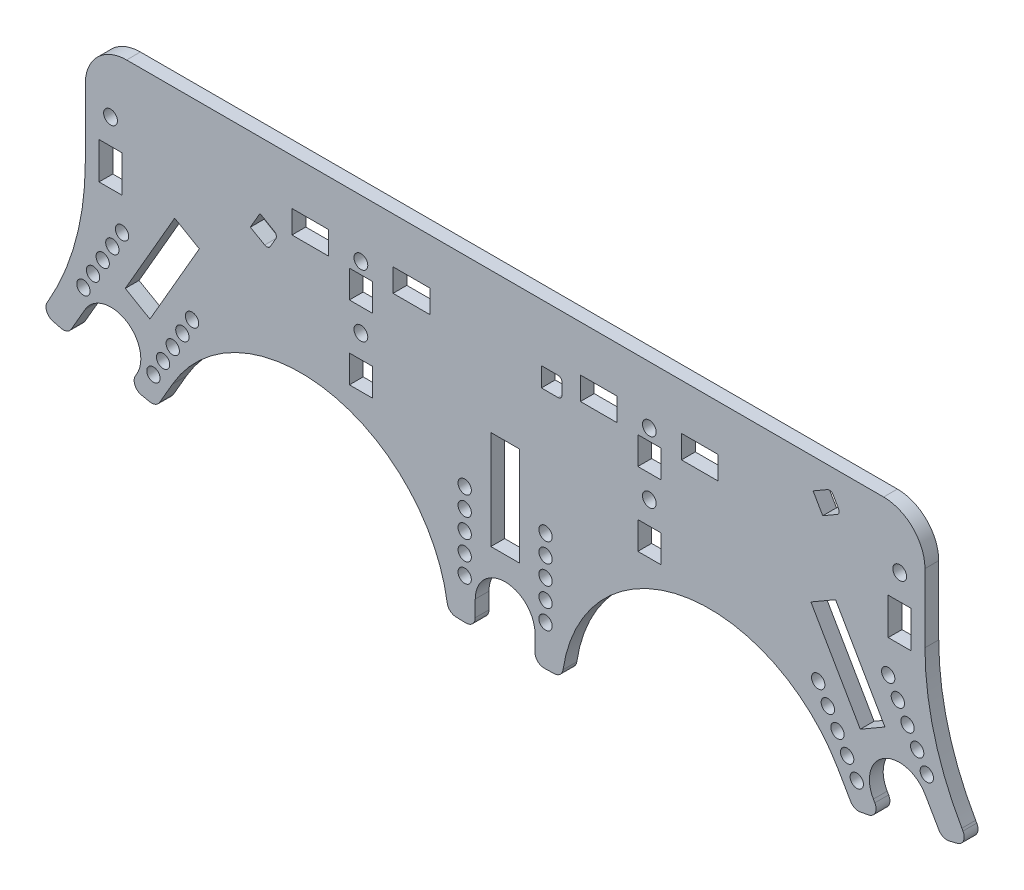
SolidWorks part; units mm, degrees
ref_plane "Front Plane" through (0, 0, 0) normal (0, 0, 1) x (1, 0, 0)
ref_plane "Top Plane" through (0, 0, 0) normal (0, 1, 0) x (1, 0, 0)
ref_plane "Right Plane" through (0, 0, 0) normal (1, 0, 0) x (0, 0, -1)
sketch "Sketch1" plane through (0, 0, 0) normal (0, 0, 1) x (1, 0, 0)
  line L0 (-12.25, 32.0854) -> (-12.25, -8)
  line L1 (-12.25, -8) -> (12.25, -8)
  line L2 (12.25, -8) -> (12.25, 32.0854)
  line L3 (12.25, 32.0854) -> (63.1039, 32.0854)
  line L4 (63.1039, 32.0854) -> (83.3912, -3.0532)
  line L5 (83.3912, -3.0532) -> (104.6088, 9.1968)
  line L6 (104.6088, 9.1968) -> (91.394, 32.0854)
  line L7 (91.394, 32.0854) -> (91.394, 72.0854)
  line L8 (91.394, 72.0854) -> (-91.394, 72.0854)
  line L9 (-91.394, 72.0854) -> (-91.394, 32.0854)
  line L10 (-91.394, 32.0854) -> (-104.6088, 9.1968)
  line L11 (-104.6088, 9.1968) -> (-83.3912, -3.0532)
  line L12 (-83.3912, -3.0532) -> (-63.1039, 32.0854)
  line L13 (-63.1039, 32.0854) -> (-12.25, 32.0854)
  line L14 (7.75, -12) -> (-7.75, -12) construction
  line L15 (102.7117, 3.4827) -> (89.2883, -4.2673) construction
  line L16 (-89.2883, -4.2673) -> (-102.7117, 3.4827) construction
  line L17 (-67.7572, 26.0256) -> (-84.5072, -2.9862) construction
  line L18 (-103.9928, 8.2638) -> (-87.2428, 37.2756) construction
  line L19 (87.2428, 37.2756) -> (103.9928, 8.2638) construction
  line L20 (84.5072, -2.9862) -> (67.7572, 26.0256) construction
  line L21 (11.25, 25) -> (11.25, -8.5) construction
  line L22 (-11.25, -8.5) -> (-11.25, 25) construction
  line L23 (-91.394, 32.0854) -> (-63.1039, 32.0854) construction
  line L24 (-12.25, 32.0854) -> (12.25, 32.0854) construction
  line L25 (63.1039, 32.0854) -> (91.394, 32.0854) construction
  line L26 (0, 72.0854) -> (0, -50.5753) construction
  circle A0 centre (0, 0) radius 33.5 construction
  circle A1 centre (-90, 10) radius 33.5 construction
  circle A2 centre (90, 10) radius 33.5 construction
  arc A3 (-72.4108, 15.9654) -> (-12.25, -0.1546) centre (-44.4901, -0.1546) cw
  arc A4 (72.4108, 15.9654) -> (12.25, -0.1546) centre (44.4901, -0.1546) ccw
  dimension "D10" = 67
  dimension "D11" = 40
  dimension "D1" = 4
  dimension "D2" = 4
  dimension "D3" = 4
  dimension "D4" = 1
  dimension "D5" = 1
  dimension "D6" = 1
  dimension "D7" = 1
  dimension "D8" = 1
  dimension "D9" = 1
extrude "Boss-Extrude1" add sketch "Sketch1" along normal blind 3 contours L12 L13 L0 L1 L2 L3 L4 L5 L6 L7 L8 L9 L10 L11 | L12 A3 L13 | L13 A3 L0 | A4 L3 L2 | A4 L4 L3
fillet "Fillet1" radius 60 2 edges at (91.394, 32.0854, 1.5) (-91.394, 32.0854, 1.5)
fillet "Fillet2" radius 8 6 edges at (-104.6088, 9.1968, 1.5) (-83.3912, -3.0532, 1.5) (-12.25, -8, 1.5) (12.25, -8, 1.5) (83.3912, -3.0532, 1.5) (104.6088, 9.1968, 1.5)
sketch "Sketch3" plane through (0, 0, 3) normal (0, 0, 1) x (1, 0, 0)
  line L8 (-53.3584, 57.6651) -> (-55.4584, 54.0278)
  line L9 (-55.4584, 54.0278) -> (-52.3407, 52.2278)
  line L10 (-51.1113, 52.5572) -> (-49.9113, 54.6357)
  line L11 (-50.2407, 55.8651) -> (-53.3584, 57.6651)
  line L12 (-53.3584, 57.6651) -> (-55.4584, 54.0278)
  line L13 (-55.4584, 54.0278) -> (-52.3407, 52.2278)
  line L14 (-51.1113, 52.5572) -> (-49.9113, 54.6357)
  line L15 (-50.2407, 55.8651) -> (-53.3584, 57.6651)
  line L16 (-68.7663, 37.5779) -> (-76.7337, 42.1779)
  line L17 (-76.7337, 42.1779) -> (-80.4837, 35.6827)
  line L18 (-80.4837, 35.6827) -> (-72.5163, 31.0827)
  line L19 (-72.5163, 31.0827) -> (-68.7663, 37.5779)
  line L20 (7.9, 59.6) -> (7.9, 55.4)
  line L21 (7.9, 55.4) -> (11.5, 55.4)
  line L22 (12.4, 56.3) -> (12.4, 58.7)
  line L23 (11.5, 59.6) -> (7.9, 59.6)
  line L24 (7.9, 59.6) -> (7.9, 55.4)
  line L25 (7.9, 55.4) -> (11.5, 55.4)
  line L26 (12.4, 56.3) -> (12.4, 58.7)
  line L27 (11.5, 59.6) -> (7.9, 59.6)
  line L32 (67.0416, 65.5651) -> (69.1416, 61.9278)
  line L33 (69.1416, 61.9278) -> (72.2593, 63.7278)
  line L34 (72.5887, 64.9572) -> (71.3887, 67.0357)
  line L35 (70.1593, 67.3651) -> (67.0416, 65.5651)
  line L36 (67.0416, 65.5651) -> (69.1416, 61.9278)
  line L37 (69.1416, 61.9278) -> (72.2593, 63.7278)
  line L38 (72.5887, 64.9572) -> (71.3887, 67.0357)
  line L39 (70.1593, 67.3651) -> (67.0416, 65.5651)
  line L40 (-68.7663, 37.5779) -> (-76.7337, 42.1779)
  line L41 (-76.7337, 42.1779) -> (-80.4837, 35.6827)
  line L42 (-80.4837, 35.6827) -> (-72.5163, 31.0827)
  line L43 (-72.5163, 31.0827) -> (-68.7663, 37.5779)
  line L48 (4.6, 34.5) -> (-4.6, 34.5)
  line L49 (-4.6, 34.5) -> (-4.6, 27)
  line L50 (-4.6, 27) -> (4.6, 27)
  line L51 (4.6, 27) -> (4.6, 34.5)
  line L52 (4.6, 34.5) -> (-4.6, 34.5)
  line L53 (-4.6, 34.5) -> (-4.6, 27)
  line L54 (-4.6, 27) -> (4.6, 27)
  line L55 (4.6, 27) -> (4.6, 34.5)
  line L60 (76.7337, 42.1779) -> (68.7663, 37.5779)
  line L61 (68.7663, 37.5779) -> (72.5163, 31.0827)
  line L62 (72.5163, 31.0827) -> (80.4837, 35.6827)
  line L63 (80.4837, 35.6827) -> (76.7337, 42.1779)
  line L64 (76.7337, 42.1779) -> (68.7663, 37.5779)
  line L65 (68.7663, 37.5779) -> (72.5163, 31.0827)
  line L66 (72.5163, 31.0827) -> (80.4837, 35.6827)
  line L67 (80.4837, 35.6827) -> (76.7337, 42.1779)
  circle A0 centre (87.596, 31.7638) radius 1.45 construction
  circle A1 centre (72.354, 22.9638) radius 1.45 construction
  circle A2 centre (8.8, 20.05) radius 1.45 construction
  circle A3 centre (-8.8, 20.05) radius 1.45 construction
  circle A4 centre (-87.596, 31.7638) radius 1.45 construction
  circle A5 centre (-72.354, 22.9638) radius 1.45 construction
  circle A6 centre (87.596, 31.7638) radius 1.45
  circle A7 centre (72.354, 22.9638) radius 1.45
  circle A8 centre (8.8, 20.05) radius 1.45
  circle A9 centre (-8.8, 20.05) radius 1.45
  circle A10 centre (-87.596, 31.7638) radius 1.45
  circle A11 centre (-72.354, 22.9638) radius 1.45
  circle A14 centre (-84.375, 19.7428) radius 3.45
  circle A15 centre (-84.375, 19.7428) radius 3.45 construction
  arc A16 (-52.3407, 52.2278) -> (-51.1113, 52.5572) centre (-51.8907, 53.0072) ccw
  arc A17 (-49.9113, 54.6357) -> (-50.2407, 55.8651) centre (-50.6907, 55.0857) ccw
  arc A18 (-52.3407, 52.2278) -> (-51.1113, 52.5572) centre (-51.8907, 53.0072) ccw
  arc A19 (-49.9113, 54.6357) -> (-50.2407, 55.8651) centre (-50.6907, 55.0857) ccw
  circle A21 centre (0, 11.25) radius 3.45
  arc A22 (11.5, 55.4) -> (12.4, 56.3) centre (11.5, 56.3) ccw
  arc A23 (12.4, 58.7) -> (11.5, 59.6) centre (11.5, 58.7) ccw
  arc A24 (11.5, 55.4) -> (12.4, 56.3) centre (11.5, 56.3) ccw
  arc A25 (12.4, 58.7) -> (11.5, 59.6) centre (11.5, 58.7) ccw
  circle A26 centre (0, 11.25) radius 3.45 construction
  arc A28 (72.2593, 63.7278) -> (72.5887, 64.9572) centre (71.8093, 64.5072) ccw
  arc A29 (71.3887, 67.0357) -> (70.1593, 67.3651) centre (70.6093, 66.5857) ccw
  arc A30 (72.2593, 63.7278) -> (72.5887, 64.9572) centre (71.8093, 64.5072) ccw
  arc A31 (71.3887, 67.0357) -> (70.1593, 67.3651) centre (70.6093, 66.5857) ccw
  circle A32 centre (84.375, 19.7428) radius 3.45
  circle A33 centre (84.375, 19.7428) radius 3.45 construction
  circle A35 centre (0, 0) radius 5.6
  circle A36 centre (0, 0) radius 5.6
  circle A38 centre (-90, 10) radius 5.6
  circle A39 centre (-90, 10) radius 5.6
  circle A41 centre (90, 10) radius 5.6
  circle A42 centre (90, 10) radius 5.6
  dimension "D1" = 0.1
  dimension "D2" = 0.1
  dimension "D3" = 0.1
  dimension "D4" = 2
  dimension "D5" = 2
  dimension "D6" = 2
  dimension "D7" = 1.5
  dimension "D8" = 1.5
  dimension "D9" = 1.5
  dimension "D10" = 2
  dimension "D11" = 2
  dimension "D12" = 2
extrude "Cut-Extrude1" cut sketch "Sketch3" against normal through all
sketch "Sketch4" plane through (0, 0, 3) normal (0, 0, 1) x (1, 0, 0)
  line L0 (84.394, 57.0854) -> (84.394, 62.0854) construction
  line L1 (29.894, 57.0854) -> (29.894, 62.0854) construction
  line L2 (32.894, 57.0854) -> (32.894, 62.0854) construction
  line L3 (87.394, 57.0854) -> (87.394, 62.0854) construction
  line L4 (-46.394, 62.0854) -> (-46.394, 57.0854)
  line L5 (-46.394, 57.0854) -> (-38.394, 57.0854)
  line L6 (-38.394, 57.0854) -> (-38.394, 62.0854)
  line L7 (-38.394, 62.0854) -> (-46.394, 62.0854)
  line L8 (-46.394, 62.0854) -> (-46.394, 57.0854)
  line L9 (-46.394, 57.0854) -> (-38.394, 57.0854)
  line L10 (-38.394, 57.0854) -> (-38.394, 62.0854)
  line L11 (-38.394, 62.0854) -> (-46.394, 62.0854)
  line L12 (-16.394, 57.0854) -> (-16.394, 62.0854)
  line L13 (-16.394, 62.0854) -> (-24.394, 62.0854)
  line L14 (-24.394, 62.0854) -> (-24.394, 57.0854)
  line L15 (-24.394, 57.0854) -> (-16.394, 57.0854)
  line L16 (-16.394, 57.0854) -> (-16.394, 62.0854)
  line L17 (-16.394, 62.0854) -> (-24.394, 62.0854)
  line L18 (-24.394, 62.0854) -> (-24.394, 57.0854)
  line L19 (-24.394, 57.0854) -> (-16.394, 57.0854)
  line L20 (16.394, 62.0854) -> (16.394, 57.0854)
  line L21 (16.394, 57.0854) -> (24.394, 57.0854)
  line L22 (24.394, 57.0854) -> (24.394, 62.0854)
  line L23 (24.394, 62.0854) -> (16.394, 62.0854)
  line L24 (16.394, 62.0854) -> (16.394, 57.0854)
  line L25 (16.394, 57.0854) -> (24.394, 57.0854)
  line L26 (24.394, 57.0854) -> (24.394, 62.0854)
  line L27 (24.394, 62.0854) -> (16.394, 62.0854)
  line L28 (46.394, 57.0854) -> (46.394, 62.0854)
  line L29 (46.394, 62.0854) -> (38.394, 62.0854)
  line L30 (38.394, 62.0854) -> (38.394, 57.0854)
  line L31 (38.394, 57.0854) -> (46.394, 57.0854)
  line L32 (46.394, 57.0854) -> (46.394, 62.0854)
  line L33 (46.394, 62.0854) -> (38.394, 62.0854)
  line L34 (38.394, 62.0854) -> (38.394, 57.0854)
  line L35 (38.394, 57.0854) -> (46.394, 57.0854)
  line L36 (-29.894, 57.0854) -> (-29.894, 62.0854) construction
  line L37 (-32.894, 57.0854) -> (-32.894, 62.0854) construction
  line L38 (-84.394, 57.0854) -> (-84.394, 62.0854) construction
  line L39 (-87.394, 57.0854) -> (-87.394, 62.0854) construction
  line L40 (-84.394, 57.0854) -> (-84.394, 62.0854) construction
  line L41 (-87.394, 57.0854) -> (-87.394, 62.0854) construction
  line L42 (84.394, 57.0854) -> (84.394, 62.0854) construction
  line L43 (-32.894, 57.0854) -> (-32.894, 62.0854) construction
  line L44 (-29.894, 57.0854) -> (-29.894, 62.0854) construction
  line L45 (87.394, 57.0854) -> (87.394, 62.0854) construction
  line L46 (32.894, 57.0854) -> (32.894, 62.0854) construction
  line L47 (29.894, 57.0854) -> (29.894, 62.0854) construction
  line L48 (-87.394, 59.5854) -> (-84.394, 59.5854) construction
  line L49 (-32.894, 59.5854) -> (-29.894, 59.5854) construction
  line L50 (29.894, 59.5854) -> (32.894, 59.5854) construction
  line L51 (84.394, 59.5854) -> (87.394, 59.5854) construction
  circle A0 centre (-31.394, 59.5854) radius 1.5
  circle A1 centre (31.394, 59.5854) radius 1.5
  circle A2 centre (-85.894, 59.5854) radius 1.5
  circle A3 centre (85.894, 59.5854) radius 1.5
  dimension "D1" = 0
  dimension "D2" = 0
  dimension "D3" = 0
  dimension "D4" = 0
extrude "Cut-Extrude2" cut sketch "Sketch4" against normal through all
sketch "Sketch5" plane through (0, 0, 3) normal (0, 0, 1) x (1, 0, 0)
  line L4 (-88.394, 54.0854) -> (-88.394, 46.0854)
  line L5 (-88.394, 46.0854) -> (-83.394, 46.0854)
  line L6 (-83.394, 46.0854) -> (-83.394, 54.0854)
  line L7 (-83.394, 54.0854) -> (-88.394, 54.0854)
  line L8 (-88.394, 54.0854) -> (-88.394, 46.0854)
  line L9 (-88.394, 46.0854) -> (-83.394, 46.0854)
  line L10 (-83.394, 46.0854) -> (-83.394, 54.0854)
  line L11 (-83.394, 54.0854) -> (-88.394, 54.0854)
  line L12 (88.394, 46.0854) -> (88.394, 54.0854)
  line L13 (88.394, 54.0854) -> (83.394, 54.0854)
  line L14 (83.394, 54.0854) -> (83.394, 46.0854)
  line L15 (83.394, 46.0854) -> (88.394, 46.0854)
  line L16 (88.394, 46.0854) -> (88.394, 54.0854)
  line L17 (88.394, 54.0854) -> (83.394, 54.0854)
  line L18 (83.394, 54.0854) -> (83.394, 46.0854)
  line L19 (83.394, 46.0854) -> (88.394, 46.0854)
  dimension "D1" = 0
  dimension "D2" = 0
extrude "Cut-Extrude3" cut sketch "Sketch5" against normal through all
fillet "Fillet3" radius 9 2 edges at (-91.394, 72.0854, 1.5) (91.394, 72.0854, 1.5)
sketch "Sketch6" plane through (0, 0, 3) normal (0, 0, 1) x (1, 0, 0)
  line L0 (-28.894, 44.5854) -> (-33.894, 44.5854) construction
  line L1 (-28.894, 47.5854) -> (-33.894, 47.5854) construction
  line L2 (28.894, 44.5854) -> (33.894, 44.5854) construction
  line L3 (28.894, 47.5854) -> (33.894, 47.5854) construction
  line L4 (33.894, 35.0854) -> (33.894, 41.0854)
  line L5 (33.894, 41.0854) -> (28.894, 41.0854)
  line L6 (28.894, 41.0854) -> (28.894, 35.0854)
  line L7 (28.894, 35.0854) -> (33.894, 35.0854)
  line L8 (33.894, 35.0854) -> (33.894, 41.0854)
  line L9 (33.894, 41.0854) -> (28.894, 41.0854)
  line L10 (28.894, 41.0854) -> (28.894, 35.0854)
  line L11 (28.894, 35.0854) -> (33.894, 35.0854)
  line L12 (33.894, 51.0854) -> (33.894, 57.0854)
  line L13 (33.894, 57.0854) -> (28.894, 57.0854)
  line L14 (28.894, 57.0854) -> (28.894, 51.0854)
  line L15 (28.894, 51.0854) -> (33.894, 51.0854)
  line L16 (33.894, 51.0854) -> (33.894, 57.0854)
  line L17 (33.894, 57.0854) -> (28.894, 57.0854)
  line L18 (28.894, 57.0854) -> (28.894, 51.0854)
  line L19 (28.894, 51.0854) -> (33.894, 51.0854)
  line L20 (-33.894, 57.0854) -> (-33.894, 51.0854)
  line L21 (-33.894, 51.0854) -> (-28.894, 51.0854)
  line L22 (-28.894, 51.0854) -> (-28.894, 57.0854)
  line L23 (-28.894, 57.0854) -> (-33.894, 57.0854)
  line L24 (-33.894, 57.0854) -> (-33.894, 51.0854)
  line L25 (-33.894, 51.0854) -> (-28.894, 51.0854)
  line L26 (-28.894, 51.0854) -> (-28.894, 57.0854)
  line L27 (-28.894, 57.0854) -> (-33.894, 57.0854)
  line L28 (-33.894, 41.0854) -> (-33.894, 35.0854)
  line L29 (-33.894, 35.0854) -> (-28.894, 35.0854)
  line L30 (-28.894, 35.0854) -> (-28.894, 41.0854)
  line L31 (-28.894, 41.0854) -> (-33.894, 41.0854)
  line L32 (-33.894, 41.0854) -> (-33.894, 35.0854)
  line L33 (-33.894, 35.0854) -> (-28.894, 35.0854)
  line L34 (-28.894, 35.0854) -> (-28.894, 41.0854)
  line L35 (-28.894, 41.0854) -> (-33.894, 41.0854)
  line L36 (-28.894, 44.5854) -> (-33.894, 44.5854) construction
  line L37 (-28.894, 47.5854) -> (-33.894, 47.5854) construction
  line L38 (28.894, 44.5854) -> (33.894, 44.5854) construction
  line L39 (28.894, 47.5854) -> (33.894, 47.5854) construction
  line L40 (-31.394, 44.5854) -> (-31.394, 47.5854) construction
  line L41 (31.394, 44.5854) -> (31.394, 47.5854) construction
  circle A0 centre (-31.394, 46.0854) radius 1.5
  circle A1 centre (31.394, 46.0854) radius 1.5
  dimension "D1" = 0
  dimension "D2" = 0
  dimension "D3" = 0
  dimension "D4" = 0
extrude "Cut-Extrude4" cut sketch "Sketch6" against normal through all
sketch "Sketch7" plane through (0, 0, 3) normal (0, 0, 1) x (1, 0, 0)
  line L3 (-75.4347, 41.4279) -> (-79.1847, 34.9327)
  line L4 (-70.0653, 38.3279) -> (-73.8153, 31.8327)
  line L5 (-72.5163, 31.0827) -> (-68.7663, 37.5779)
  line L6 (-80.4837, 35.6827) -> (-72.5163, 31.0827)
  line L7 (-76.7337, 42.1779) -> (-80.4837, 35.6827)
  line L8 (-68.7663, 37.5779) -> (-76.7337, 42.1779)
  line L9 (-72.5163, 31.0827) -> (-68.7663, 37.5779)
  line L10 (-80.4837, 35.6827) -> (-72.5163, 31.0827)
  line L11 (-76.7337, 42.1779) -> (-80.4837, 35.6827)
  line L12 (-68.7663, 37.5779) -> (-76.7337, 42.1779)
  line L13 (-3.1, 34.5) -> (-3.1, 27)
  line L14 (4.6, 27) -> (4.6, 34.5)
  line L15 (-4.6, 27) -> (4.6, 27)
  line L16 (-4.6, 34.5) -> (-4.6, 27)
  line L17 (4.6, 34.5) -> (-4.6, 34.5)
  line L18 (4.6, 27) -> (4.6, 34.5)
  line L19 (-4.6, 27) -> (4.6, 27)
  line L20 (-4.6, 34.5) -> (-4.6, 27)
  line L21 (4.6, 34.5) -> (-4.6, 34.5)
  line L22 (3.1, 34.5) -> (3.1, 27)
  line L23 (80.4837, 35.6827) -> (76.7337, 42.1779)
  line L24 (72.5163, 31.0827) -> (80.4837, 35.6827)
  line L25 (68.7663, 37.5779) -> (72.5163, 31.0827)
  line L26 (76.7337, 42.1779) -> (68.7663, 37.5779)
  line L27 (80.4837, 35.6827) -> (76.7337, 42.1779)
  line L28 (72.5163, 31.0827) -> (80.4837, 35.6827)
  line L29 (68.7663, 37.5779) -> (72.5163, 31.0827)
  line L30 (76.7337, 42.1779) -> (68.7663, 37.5779)
  line L31 (70.0653, 38.3279) -> (73.8153, 31.8327)
  line L32 (75.4347, 41.4279) -> (79.1847, 34.9327)
  dimension "D4" = 1.5
  dimension "D5" = 1.5
  dimension "D6" = 1.5
  dimension "D7" = 1.5
  dimension "D8" = 1.5
  dimension "D9" = 1.5
  dimension "D1" = 0
  dimension "D2" = 0
  dimension "D3" = 0
extrude "Boss-Extrude2" add sketch "Sketch7" against normal blind 3 contours L3 L12 L11 L10 | L9 L12 L4 L10 | L13 L21 L20 L19 | L21 L22 L19 L18 | L31 L30 L29 L28 | L30 L32 L28 L27
sketch "Sketch8" plane through (0, 0, 3) normal (0, 0, 1) x (1, 0, 0)
  line L0 (-8.8, 20.05) -> (-8.8, 2.5535) construction
  line L1 (-8.8, 2.5535) -> (-8.8, 55.0937) construction
  line L2 (8.8, 20.05) -> (8.8, 2.5535) construction
  line L3 (8.8, 2.5535) -> (8.8, 53.2094) construction
  line L4 (-94, 3.0718) -> (-76.5, 33.3827) construction
  line L5 (-97.6806, 5.1968) -> (-90.3194, 0.9468) construction
  line L6 (-79.1847, 34.9327) -> (-73.8153, 31.8327) construction
  line L7 (-72.354, 22.9638) -> (-81.927, 6.3828) construction
  line L8 (-81.927, 6.3828) -> (-61.3854, 41.9619) construction
  line L9 (-87.596, 31.7638) -> (-96.7852, 15.8477) construction
  line L10 (-96.7852, 15.8477) -> (-75.9419, 51.9493) construction
  line L11 (94, 3.0718) -> (76.5, 33.3827) construction
  line L12 (90.3194, 0.9468) -> (97.6806, 5.1968) construction
  line L13 (73.8153, 31.8327) -> (79.1847, 34.9327) construction
  line L14 (72.354, 22.9638) -> (62.3503, 40.2908) construction
  line L15 (62.3503, 40.2908) -> (89.4496, -6.6466) construction
  line L16 (87.596, 31.7638) -> (106.5379, -1.0444) construction
  line L17 (106.5379, -1.0444) -> (78.5925, 47.3584) construction
  line L18 (-8.8, 20.05) -> (-8.8, 15.85) construction
  line L19 (-72.354, 22.9638) -> (-74.454, 19.3265) construction
  line L20 (0, 34.5) -> (0, 0) construction
  line L21 (3.1, 34.5) -> (-3.1, 34.5) construction
  line L22 (0, 0) -> (21.2479, -3.7728) construction
  line L23 (72.354, 22.9638) -> (74.454, 19.3265) construction
  line L24 (8.8, 20.05) -> (8.8, 15.85) construction
  line L25 (96.7852, 15.8477) -> (75.9419, 51.9493) construction
  line L26 (87.596, 31.7638) -> (96.7852, 15.8477) construction
  line L27 (81.927, 6.3828) -> (61.3854, 41.9619) construction
  line L28 (72.354, 22.9638) -> (81.927, 6.3828) construction
  line L29 (94, 3.0718) -> (76.5, 33.3827) construction
  line L30 (8.8, 2.5535) -> (8.8, 55.0937) construction
  line L31 (8.8, 20.05) -> (8.8, 2.5535) construction
  circle A0 centre (-8.8, 20.05) radius 1.45 construction
  circle A1 centre (-8.8, 20.05) radius 1.45 construction
  circle A2 centre (-8.8, 15.85) radius 1.45
  circle A3 centre (-8.8, 11.65) radius 1.45
  circle A4 centre (-8.8, 20.05) radius 1.45
  circle A5 centre (-8.8, 15.85) radius 1.45
  circle A6 centre (-8.8, 24.25) radius 1.45
  circle A7 centre (-8.8, 20.05) radius 1.45
  circle A8 centre (-8.8, 24.25) radius 1.45
  circle A9 centre (-8.8, 28.45) radius 1.45
  circle A10 centre (-72.354, 22.9638) radius 1.45 construction
  circle A11 centre (-72.354, 22.9638) radius 1.45 construction
  circle A12 centre (-74.454, 19.3265) radius 1.45
  circle A13 centre (-76.554, 15.6892) radius 1.45
  circle A14 centre (-72.354, 22.9638) radius 1.45
  circle A15 centre (-74.454, 19.3265) radius 1.45
  circle A16 centre (-70.254, 26.6011) radius 1.45
  circle A17 centre (-72.354, 22.9638) radius 1.45
  circle A18 centre (-70.254, 26.6011) radius 1.45
  circle A19 centre (-68.154, 30.2384) radius 1.45
  circle A20 centre (-91.796, 24.4892) radius 1.45
  circle A21 centre (-89.696, 28.1265) radius 1.45
  circle A22 centre (-85.496, 35.4011) radius 1.45
  circle A23 centre (-83.396, 39.0384) radius 1.45
  circle A24 centre (83.396, 39.0384) radius 1.45
  circle A25 centre (85.496, 35.4011) radius 1.45
  circle A26 centre (89.696, 28.1265) radius 1.45
  circle A27 centre (91.796, 24.4892) radius 1.45
  circle A28 centre (68.154, 30.2384) radius 1.45
  circle A29 centre (70.254, 26.6011) radius 1.45
  circle A30 centre (72.354, 22.9638) radius 1.45 construction
  circle A31 centre (70.254, 26.6011) radius 1.45
  circle A32 centre (74.454, 19.3265) radius 1.45
  circle A33 centre (72.354, 22.9638) radius 1.45
  circle A34 centre (76.554, 15.6892) radius 1.45
  circle A35 centre (74.454, 19.3265) radius 1.45
  circle A36 centre (72.354, 22.9638) radius 1.45
  circle A37 centre (8.8, 28.45) radius 1.45
  circle A38 centre (8.8, 24.25) radius 1.45
  circle A39 centre (8.8, 20.05) radius 1.45 construction
  circle A40 centre (8.8, 24.25) radius 1.45
  circle A41 centre (8.8, 15.85) radius 1.45
  circle A42 centre (8.8, 20.05) radius 1.45
  circle A43 centre (8.8, 11.65) radius 1.45
  circle A44 centre (8.8, 15.85) radius 1.45
  circle A45 centre (8.8, 20.05) radius 1.45
  dimension "D1" = 3
  dimension "D3" = 4.2
  dimension "D6" = 4.2
  dimension "D2" = 3
  dimension "D4" = 3
  dimension "D5" = 3
extrude "Cut-Extrude5" cut sketch "Sketch8" against normal through all contours A34 | A32 | A27 | A26 | A25 | A24 | A28 | A9 | A6 | A2 | A43 | A41 | A3 | A38 | A37 | A16 | A19 | A12 | A13 | A22 | A23 | A21 | A20 | A29
sketch "Sketch9" plane through (0, 0, 3) normal (0, 0, 1) x (1, 0, 0)
  line L0 (-94, 3.0718) -> (-57.2367, 66.7477) construction
  line L1 (-97.6806, 5.1968) -> (-90.3194, 0.9468) construction
  line L2 (0, -8) -> (0, 59.0784) construction
  line L3 (-4.2503, -8) -> (4.2503, -8) construction
  line L4 (94, 3.0718) -> (60.9426, 61.086) construction
  line L5 (90.3194, 0.9468) -> (97.6806, 5.1968) construction
  line L6 (-75.4347, 41.4279) -> (-71.9347, 47.4901)
  line L7 (-71.9347, 47.4901) -> (-66.5653, 44.3901)
  line L8 (-66.5653, 44.3901) -> (-70.0653, 38.3279)
  line L9 (-70.0653, 38.3279) -> (-75.4347, 41.4279)
  line L10 (-79.1847, 34.9327) -> (-73.8153, 31.8327)
  line L11 (-73.8153, 31.8327) -> (-77.3153, 25.7705)
  line L12 (-77.3153, 25.7705) -> (-82.6847, 28.8705)
  line L13 (-82.6847, 28.8705) -> (-79.1847, 34.9327)
  line L14 (-70.0653, 38.3279) -> (-73.8153, 31.8327) construction
  line L15 (-75.4347, 41.4279) -> (-79.1847, 34.9327) construction
  line L16 (-88.5708, -0.5246) -> (-80.1708, 14.0246)
  line L17 (-99.8292, 5.9754) -> (-91.4292, 20.5246)
  line L18 (-6.5, 8.4) -> (-6.5, -8.4)
  line L19 (-3.1, 34.5) -> (3.1, 34.5)
  line L20 (-3.1, 34.5) -> (-3.1, 41.5)
  line L21 (-3.1, 41.5) -> (3.1, 41.5)
  line L22 (3.1, 34.5) -> (3.1, 41.5)
  line L23 (-3.1, 27) -> (3.1, 27)
  line L24 (-3.1, 27) -> (-3.1, 20)
  line L25 (-3.1, 20) -> (3.1, 20)
  line L26 (3.1, 27) -> (3.1, 20)
  line L27 (6.5, 8.4) -> (6.5, -8.4)
  line L28 (99.8292, 5.9754) -> (91.4292, 20.5246)
  line L29 (88.5708, -0.5246) -> (80.1708, 14.0246)
  line L30 (82.6847, 28.8705) -> (79.1847, 34.9327)
  line L31 (77.3153, 25.7705) -> (82.6847, 28.8705)
  line L32 (73.8153, 31.8327) -> (77.3153, 25.7705)
  line L33 (79.1847, 34.9327) -> (73.8153, 31.8327)
  line L34 (70.0653, 38.3279) -> (75.4347, 41.4279)
  line L35 (66.5653, 44.3901) -> (70.0653, 38.3279)
  line L36 (71.9347, 47.4901) -> (66.5653, 44.3901)
  line L37 (75.4347, 41.4279) -> (71.9347, 47.4901)
  circle A0 centre (-90, 10) radius 6.5
  circle A1 centre (-94.2, 2.7254) radius 6.5
  circle A2 centre (-85.8, 17.2746) radius 6.5
  circle A3 centre (0, 0) radius 6.5
  circle A4 centre (0, 8.4) radius 6.5
  circle A5 centre (0, -8.4) radius 6.5
  circle A6 centre (85.8, 17.2746) radius 6.5
  circle A7 centre (94.2, 2.7254) radius 6.5
  circle A8 centre (90, 10) radius 6.5
  dimension "D3" = 13
  dimension "D4" = 8.4
  dimension "D6" = 8.4
  dimension "D1" = 7
  dimension "D2" = 7
  dimension "D5" = 8.4
  dimension "D7" = 8.4
extrude "Cut-Extrude6" cut sketch "Sketch9" against normal blind 3 contours L9 L8 L7 L6 | L13 L12 L11 L10 | A2 A0 | A0 A2 | A2 A0 A1 | A0 A1 | A0 A1 | A1 A0 L17 | A2 L17 A0 | A2 A0 L16 | A1 L16 A0 | L19 L22 L21 L20 | L26 L23 L24 L25 | A4 A3 | A5 A3 A4 | A3 A4 | A3 A5 | A5 A3 | A5 L27 A3 | A4 A3 L27 | A4 L18 A3 | A5 A3 L18 | L34 L37 L36 L35 | L30 L33 L32 L31 | A6 A8 | A8 A7 A6 | A8 A6 | A8 A7 | A7 A8 | L28 A8 A7 | A6 A8 L28 | L29 A8 A6 | A7 A8 L29
sketch "Sketch10" plane through (0, 0, 3) normal (0, 0, 1) x (1, 0, 0)
  line L0 (0, 72.0854) -> (0, 165.9817) construction
  line L1 (82.394, 72.0854) -> (-82.394, 72.0854) construction
  line L2 (-122.9043, 21.6903) -> (-108.9651, -45.8011)
  line L3 (-108.9651, -45.8011) -> (156.2449, -40.1864)
  line L4 (156.2449, -40.1864) -> (133.6255, 25.2323)
  circle A0 centre (0, 411.6968) radius 408.9138
extrude "Cut-Extrude7" cut sketch "Sketch10" against normal blind 3 contours A0 L2 L3 L4
fillet "Fillet4" radius 2 12 edges at (100.9604, 15.4424, 1.5) (81.8799, 11.0645, 1.5) (12.4019, 2.9711, 1.5) (-6.5, 2.8346, 1.5) (-12.4019, 2.9711, 1.5) (6.5, 2.8346, 1.5) (95.1869, 14.016, 1.5) (75.9173, 9.892, 1.5) (-75.9173, 9.892, 1.5) (-81.8799, 11.0645, 1.5) (-95.1869, 14.016, 1.5) (-100.9604, 15.4424, 1.5)
